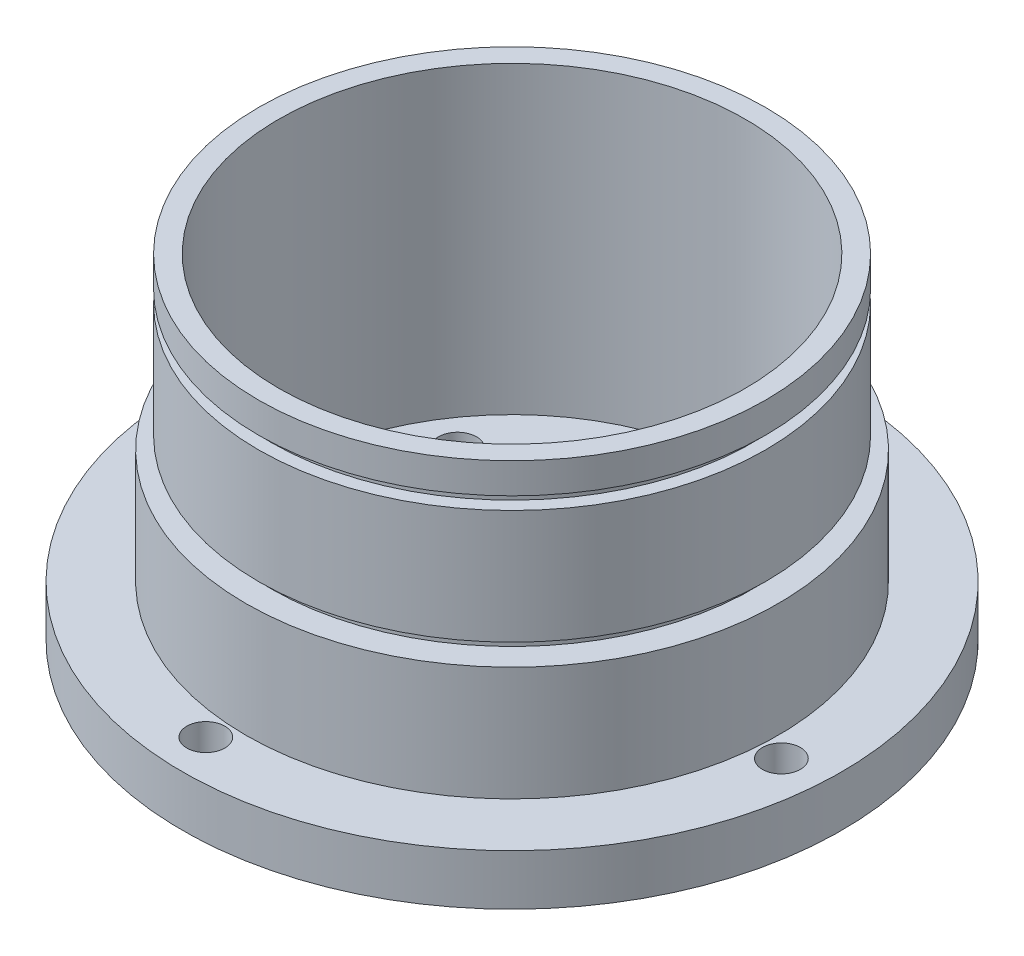
SolidWorks part; units mm, degrees
ref_plane "前视基准面" through (0, 0, 0) normal (0, 0, 1) x (1, 0, 0)
ref_plane "上视基准面" through (0, 0, 0) normal (0, 1, 0) x (1, 0, 0)
ref_plane "右视基准面" through (0, 0, 0) normal (1, 0, 0) x (0, 0, -1)
sketch "草图1" plane through (0, 0, 0) normal (0, 1, 0) x (1, 0, 0)
  circle A0 centre (0, 0) radius 21
  dimension "D1" = 42
extrude "凸台-拉伸2" add sketch "草图1" along normal blind 26.4
sketch "草图10" plane through (0, 26.4, 0) normal (0, 1, 0) x (1, 0, 0)
  circle A0 centre (0, 0) radius 18.4
extrude "切除-拉伸5" cut sketch "草图10" against normal blind 24
sketch "草图11" plane through (0, 0, 0) normal (0, -1, 0) x (1, 0, 0)
  circle A0 centre (-0.993, 15.4682) radius 1.5
  circle A1 centre (12.8993, 8.5941) radius 1.5
  circle A2 centre (13.8923, -6.8741) radius 1.5
  circle A3 centre (0.993, -15.4682) radius 1.5
  circle A4 centre (-12.8993, -8.5941) radius 1.5
  circle A5 centre (-13.8923, 6.8741) radius 1.5
  point P15 (0, 0)
  dimension "D1" = 6
extrude "切除-拉伸6" cut sketch "草图11" against normal blind 24
sketch "草图12" plane through (0, 0, 0) normal (1, 0, 0) x (0, 0, -1)
  line L0 (0, 0) -> (0, 4)
  line L1 (0, 4) -> (6.6327, 4)
ref_plane "基准面2" through (0, 4, 0) normal (0, -1, 0) x (-1, 0, 0)
sketch "草图13" plane through (0, 4, 0) normal (0, -1, 0) x (-1, 0, 0)
  circle A0 centre (0, 0) radius 21
  circle A1 centre (0, 0) radius 24.5
extrude "凸台-拉伸4" add sketch "草图13" along normal blind 4
sketch "草图14" plane through (0, 4, 0) normal (0, 1, 0) x (1, 0, 0)
  circle A0 centre (1.4575, 22.7033) radius 1.5
  circle A1 centre (22.7033, -1.4575) radius 1.5
  circle A2 centre (-1.4575, -22.7033) radius 1.5
  circle A3 centre (-22.7033, 1.4575) radius 1.5
  point P12 (0, 0)
  dimension "D1" = 4
extrude "切除-拉伸7" cut sketch "草图14" against normal blind 4
sketch "草图15" plane through (0, 0, 0) normal (1, 0, 0) x (0, 0, -1)
  line L0 (0, 4) -> (0, 13)
  line L1 (0, 13) -> (-11.7465, 13)
ref_plane "基准面3" through (0, 13, 0) normal (0, -1, 0) x (-1, 0, 0)
sketch "草图16" plane through (0, 13, 0) normal (0, -1, 0) x (-1, 0, 0)
  circle A1 centre (0, 0) radius 21
  circle A2 centre (0, 0) radius 19
extrude "切除-拉伸10" cut sketch "草图16" against normal blind 1
sketch "草图20" plane through (0, 0, 0) normal (0, 0, 1) x (1, 0, 0)
  line L0 (0, 14) -> (0, 23)
  line L1 (-19, 14) -> (19, 14) construction
  line L2 (0, 23) -> (14.3, 23)
  dimension "D1" = 9
ref_plane "基准面5" through (0, 23, 0) normal (0, -1, 0) x (-1, 0, 0)
sketch "草图25" plane through (0, 0, 0) normal (0, 0, 1) x (1, 0, 0)
  line L0 (0, 14) -> (0, 24.2655)
sketch "草图27" plane through (0, 14, 0) normal (0, -1, 0) x (1, 0, 0)
  circle A0 centre (0, 0) radius 20
  circle A1 centre (0, 0) radius 21
  dimension "D1" = 40
extrude "切除-拉伸14" cut sketch "草图27" against normal blind 20
ref_plane "基准面6" through (0, 24.2655, 0) normal (0, -1, 0) x (-1, 0, 0)
ref_plane "基准面7" through (0, 23, 0) normal (0, -1, 0) x (-1, 0, 0)
sketch "草图29" plane through (0, 23, 0) normal (0, -1, 0) x (-1, 0, 0)
  circle A0 centre (0, 0) radius 19
  circle A2 centre (0, 0) radius 20
  circle A3 centre (0, 0) radius 20
  dimension "D1" = 0
extrude "切除-拉伸15" cut sketch "草图29" against normal blind 1
sketch "草图31" plane through (0, 0, 0) normal (0, -1, 0) x (1, 0, 0)
  line L1 (7, 0) -> (-6.4014, 0) construction
  line L2 (7, -6.0188) -> (-6.4014, -6.0188)
  line L3 (7, 6.0188) -> (-6.4014, 6.0188)
  arc A2 (7, -6.0188) -> (7, 6.0188) centre (7, 0) ccw
  arc A3 (-6.4014, 6.0188) -> (-6.4014, -6.0188) centre (-6.4014, 0) ccw
  point P5 (0.2993, 0)
  dimension "D1" = 13.4014
extrude "切除-拉伸16" cut sketch "草图31" against normal blind 10
sketch "草图32" plane through (0, 0, 0) normal (0, -1, 0) x (1, 0, 0)
  circle A0 centre (0, 0) radius 26
  circle A1 centre (0, 0) radius 24.5
extrude "凸台-拉伸5" add sketch "草图32" against normal blind 4
